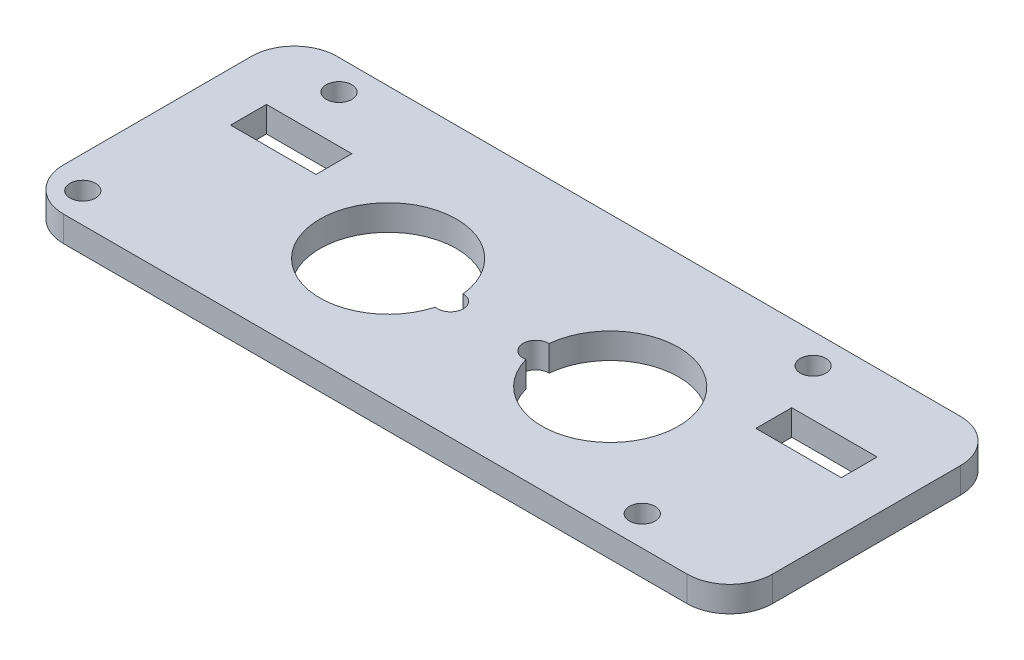
SolidWorks part; units mm, degrees
ref_plane "Front Plane" through (0, 0, 0) normal (0, 0, 1) x (1, 0, 0)
ref_plane "Top Plane" through (0, 0, 0) normal (0, 1, 0) x (1, 0, 0)
ref_plane "Right Plane" through (0, 0, 0) normal (1, 0, 0) x (0, 0, -1)
sketch "Sketch1" plane through (0, 0, 0) normal (0, 1, 0) x (1, 0, 0)
  line L1 (47.5, 17.5) -> (-47.5, 17.5)
  line L2 (47.5, 17.5) -> (47.5, -17.5)
  line L3 (47.5, -17.5) -> (-47.5, -17.5)
  line L4 (-47.5, 17.5) -> (-47.5, -17.5)
  line L5 (47.5, 17.5) -> (-47.5, -17.5) construction
  line L6 (47.5, -17.5) -> (-47.5, 17.5) construction
  point P0 (-27.5, 12.5)
  point P1 (27.5, 12.5)
  point P2 (32.5, -12.5)
  point P4 (-32.5, -12.5)
  point P7 (0, 0)
  dimension "D1" = 55
  dimension "D2" = 27.5
  dimension "D3" = 65
  dimension "D4" = 32.5
  dimension "D5" = 12.5
  dimension "D6" = 12.5
  dimension "D7" = 30
  dimension "D8" = 15
extrude "Boss-Extrude1" add sketch "Sketch1" along normal blind 3
sketch "Sketch2" plane through (0, 0, 0) normal (0, 1, 0) x (1, 0, 0)
  line L0 (-60, 27.5) -> (60, 27.5)
  circle A0 centre (-42.5, -12.5) radius 1.5 construction
  dimension "D1" = 40
  dimension "D2" = 120
  dimension "D3" = 60
  dimension "D4" = 45
  dimension "D5" = 45
sketch "Sketch3" plane through (0, 0, 0) normal (0, -1, 0) x (1, 0, 0)
  line L0 (-47.5, 17.5) -> (47.5, 17.5) construction
  circle A0 centre (-13, 1.5) radius 8
  circle A1 centre (13, 1.5) radius 8
  dimension "D1" = 16
  dimension "D2" = 16
  dimension "D3" = 16
  dimension "D4" = 26
  dimension "D5" = 13
extrude "Cut-Extrude1" cut sketch "Sketch3" against normal up to next
sketch "Sketch4" plane through (0, 0, 0) normal (0, 1, 0) x (1, 0, 0)
  line L5 (-47.5, -17.5) -> (47.5, -17.5) construction
  line L6 (-47.5, 17.5) -> (-47.5, -17.5) construction
  line L11 (47.5, 17.5) -> (-47.5, 17.5) construction
  line L12 (47.5, -17.5) -> (47.5, 17.5) construction
  circle A0 centre (-37.75, -12.5) radius 1.5
  circle A1 centre (27.75, -12.5) radius 1.5
  circle A2 centre (22.75, 12.5) radius 1.5
  circle A3 centre (-32.75, 12.5) radius 1.5
  point P0 (-32.75, -12.5)
  point P5 (32.75, -12.5)
  point P10 (27.75, 12.5)
  point P15 (-27.75, 12.5)
  point P20 (-32.75, -12.5)
  point P29 (32.75, -12.5)
  point P30 (-32.75, -12.5)
  point P31 (27.75, 12.5)
  point P32 (-27.75, 12.5)
  dimension "D9" = 3
  dimension "D10" = 3
  dimension "D11" = 3
  dimension "D12" = 3
  dimension "D1" = 5
  dimension "D2" = 14.75
  dimension "D3" = 19.75
  dimension "D4" = 5
  dimension "D5" = 5
  dimension "D6" = 19.75
  dimension "D7" = 14.75
  dimension "D8" = 5
  dimension "D13" = 5
  dimension "D14" = 5
  dimension "D15" = 5
  dimension "D16" = 5
extrude "Cut-Extrude2" cut sketch "Sketch4" along normal up to next
sketch "Sketch5" plane through (0, 0, 0) normal (0, 1, 0) x (1, 0, 0)
  line L0 (47.5, 17.5) -> (-47.5, 17.5) construction
  line L1 (-47.5, -21.5) -> (47.5, -21.5)
  line L2 (-47.5, -21.5) -> (-47.5, -17.5)
  line L3 (-47.5, -17.5) -> (47.5, -17.5)
  line L4 (47.5, -21.5) -> (47.5, -17.5)
  line L5 (-47.5, -21.5) -> (47.5, -17.5) construction
  line L6 (-47.5, -17.5) -> (47.5, -21.5) construction
  line L7 (-47.5, 17.5) -> (47.5, 17.5)
  line L8 (-47.5, 17.5) -> (-47.5, 21.5)
  line L9 (-47.5, 21.5) -> (47.5, 21.5)
  line L10 (47.5, 17.5) -> (47.5, 21.5)
  line L11 (-47.5, 17.5) -> (47.5, 21.5) construction
  line L12 (-47.5, 21.5) -> (47.5, 17.5) construction
  line L13 (-47.5, -17.5) -> (47.5, -17.5) construction
  point P0 (0, -19.5)
  point P5 (0, 19.5)
  dimension "D1" = 4
  dimension "D2" = 4
extrude "Boss-Extrude2" add sketch "Sketch5" along normal blind 3
sketch "Sketch6" plane through (0, 0, 0) normal (0, 1, 0) x (1, 0, 0)
  line L0 (19.75, 7) -> (35.75, 7) construction
  line L1 (-35.75, 2.8) -> (-25.75, 2.8)
  line L2 (-35.75, 2.8) -> (-35.75, 7)
  line L3 (-35.75, 7) -> (-25.75, 7)
  line L4 (-25.75, 2.8) -> (-25.75, 7)
  line L5 (-35.75, 2.8) -> (-25.75, 7) construction
  line L6 (-35.75, 7) -> (-25.75, 2.8) construction
  line L7 (25.75, 2.8) -> (35.75, 2.8)
  line L8 (25.75, 2.8) -> (25.75, 7)
  line L9 (25.75, 7) -> (35.75, 7)
  line L10 (35.75, 2.8) -> (35.75, 7)
  line L11 (25.75, 2.8) -> (35.75, 7) construction
  line L12 (25.75, 7) -> (35.75, 2.8) construction
  line L13 (47.5, 21.5) -> (-47.5, 21.5) construction
  line L15 (-47.5, 21.5) -> (-47.5, -21.5) construction
  line L16 (47.5, -21.5) -> (47.5, 21.5) construction
  point P0 (-30.75, 4.9)
  point P5 (30.75, 4.9)
  dimension "D1" = 4.2
  dimension "D2" = 10
  dimension "D3" = 4.2
  dimension "D4" = 10
  dimension "D5" = 14.5
  dimension "D6" = 11.75
  dimension "D7" = 11.75
  dimension "D8" = 14.5
extrude "Cut-Extrude3" cut sketch "Sketch6" along normal up to next
sketch "Sketch7" plane through (0, 0, 0) normal (0, -1, 0) x (1, 0, 0)
  circle A0 centre (-5, 2.2011) radius 1.5
  circle A1 centre (5, 2.2011) radius 1.5
  dimension "D3" = 3
  dimension "D4" = 3
  dimension "D1" = 5
  dimension "D2" = 5
extrude "Cut-Extrude4" cut sketch "Sketch7" against normal up to next
sketch "Sketch8" plane through (0, 0, 0) normal (0, 1, 0) x (1, 0, 0)
  line L1 (-41.5, 16) -> (41.5, 16)
  line L2 (-41.5, 16) -> (-41.5, -16)
  line L3 (-41.5, -16) -> (41.5, -16)
  line L4 (41.5, 16) -> (41.5, -16)
  line L5 (-41.5, 16) -> (41.5, -16) construction
  line L6 (-41.5, -16) -> (41.5, 16) construction
  line L7 (-52.7696, 25.8223) -> (52.7696, 25.8223)
  line L8 (-52.7696, 25.8223) -> (-52.7696, -25.8223)
  line L9 (-52.7696, -25.8223) -> (52.7696, -25.8223)
  line L10 (52.7696, 25.8223) -> (52.7696, -25.8223)
  line L11 (-52.7696, 25.8223) -> (52.7696, -25.8223) construction
  line L12 (-52.7696, -25.8223) -> (52.7696, 25.8223) construction
  point P0 (0, 0)
  point P6 (0, 0)
  dimension "D1" = 83
  dimension "D2" = 32
extrude "Cut-Extrude5" cut sketch "Sketch8" along normal up to next
fillet "Fillet1" radius 5 4 edges at (-41.5, 1.5, 16) (41.5, 1.5, 16) (41.5, 1.5, -16) (-41.5, 1.5, -16)
